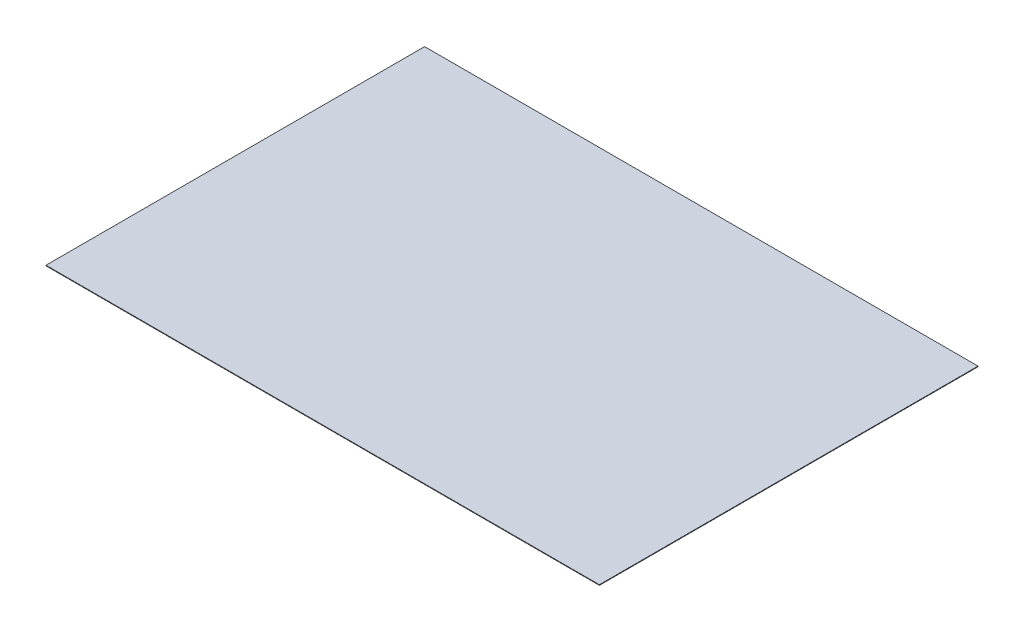
SolidWorks part; units mm, degrees
ref_plane "Ebene vorne" through (0, 0, 0) normal (0, 0, 1) x (1, 0, 0)
ref_plane "Ebene oben" through (0, 0, 0) normal (0, 1, 0) x (1, 0, 0)
ref_plane "Ebene rechts" through (0, 0, 0) normal (1, 0, 0) x (0, 0, -1)
sketch "Skizze1" plane through (0, 0, 0) normal (0, 1, 0) x (1, 0, 0)
  line L1 (0, 0) -> (95, 0)
  line L2 (0, 0) -> (0, 65)
  line L3 (0, 65) -> (95, 65)
  line L4 (95, 0) -> (95, 65)
  dimension "D1" = 95
  dimension "D2" = 65
extrude "Aufsatz-Linear austragen1" add sketch "Skizze1" along normal blind 0.1
